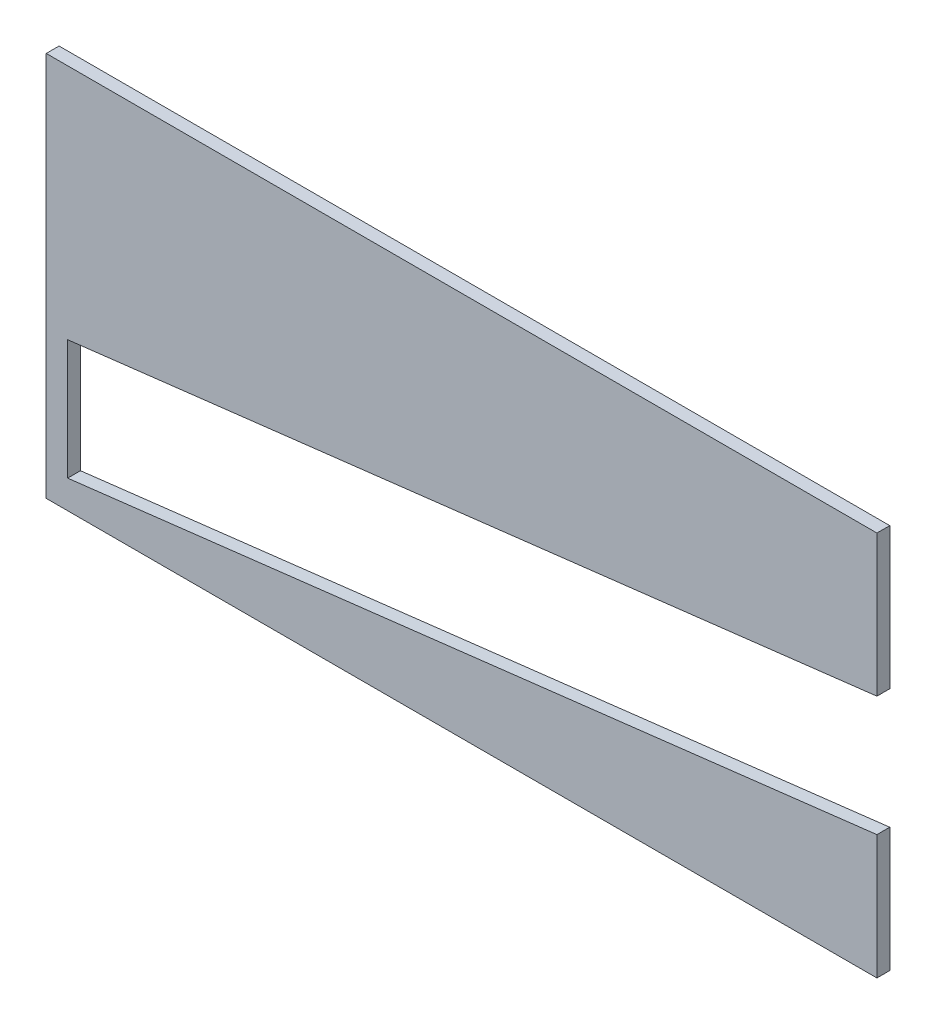
SolidWorks part; units mm, degrees
ref_plane "前基準面" through (0, 0, 0) normal (0, 0, 1) x (1, 0, 0)
ref_plane "上基準面" through (0, 0, 0) normal (0, 1, 0) x (1, 0, 0)
ref_plane "右基準面" through (0, 0, 0) normal (1, 0, 0) x (0, 0, -1)
sketch "草圖1" plane through (0, 0, 0) normal (0, 0, 1) x (1, 0, 0)
  line L0 (-90.6822, -39.4412) -> (-90.6822, -11.4412)
  line L1 (-95.6822, 43.9588) -> (98.3178, 43.9588)
  line L2 (-95.6822, 43.9588) -> (-95.6822, -46.0412)
  line L3 (-95.6822, -46.0412) -> (98.3178, -46.0412)
  line L4 (98.3178, 43.9588) -> (98.3178, 10.9588)
  line L5 (-90.6822, -39.4412) -> (98.3178, -17.0412)
  line L6 (-90.6822, -11.4412) -> (98.3178, 10.9588)
  line L8 (98.3178, -17.0412) -> (98.3178, -46.0412)
  dimension "D1" = 194
  dimension "D2" = 90
  dimension "D3" = 29
  dimension "D4" = 6.6
  dimension "D5" = 5
  dimension "D6" = 28
extrude "填料-伸長1" add sketch "草圖1" along normal blind 3 contours L1 L4 L6 L0 L5 L8 L3 L2
